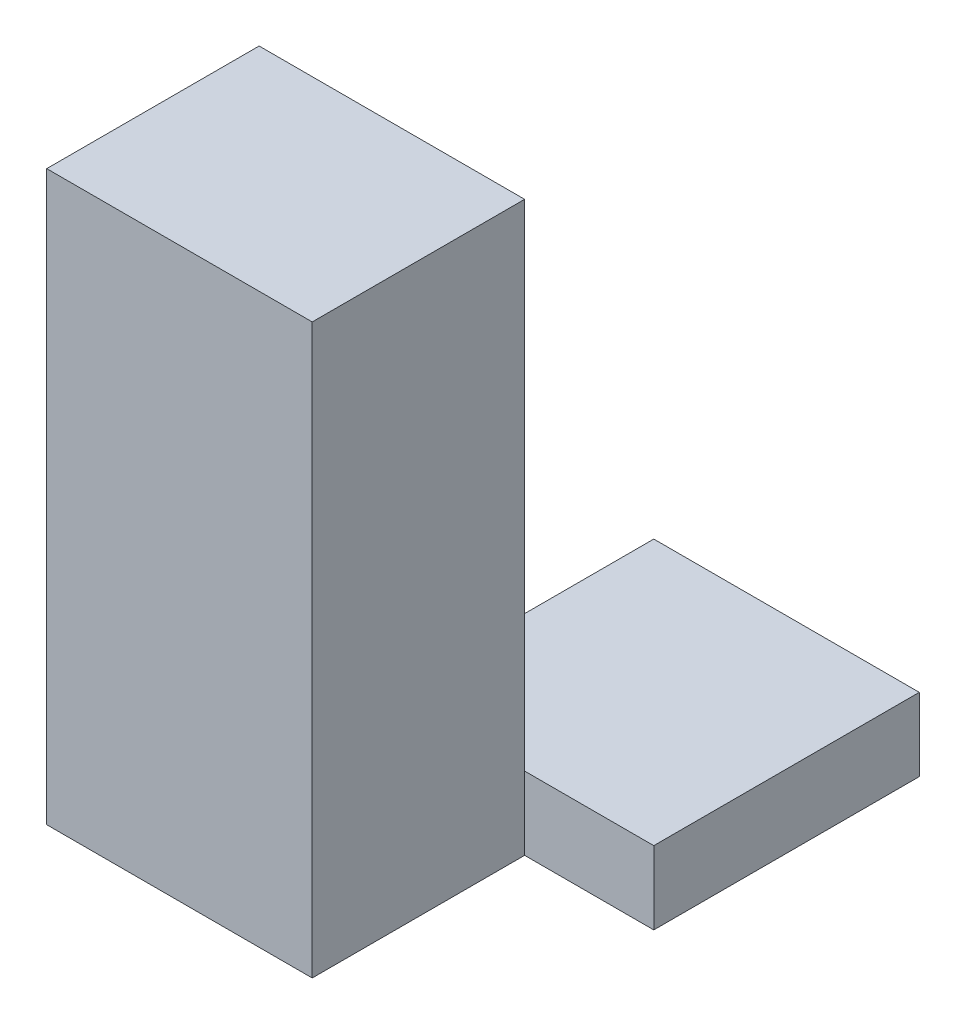
SolidWorks part; units mm, degrees
ref_plane "Front Plane" through (0, 0, 0) normal (0, 0, 1) x (1, 0, 0)
ref_plane "Top Plane" through (0, 0, 0) normal (0, 1, 0) x (1, 0, 0)
ref_plane "Right Plane" through (0, 0, 0) normal (1, 0, 0) x (0, 0, -1)
sketch "Sketch1" plane through (0, 0, 0) normal (0, 0, 1) x (1, 0, 0)
  line L1 (-19.457, -57.7267) -> (20.543, -57.7267)
  line L2 (-19.457, -57.7267) -> (-19.457, 27.8733)
  line L3 (-19.457, 27.8733) -> (20.543, 27.8733)
  line L4 (20.543, -57.7267) -> (20.543, 27.8733)
  line L5 (-19.457, -57.7267) -> (20.543, 27.8733) construction
  line L6 (-19.457, 27.8733) -> (20.543, -57.7267) construction
  point P0 (0.543, -14.9267)
  dimension "D1" = 40
  dimension "D2" = 85.6
extrude "Boss-Extrude1" add sketch "Sketch1" along normal blind 32
sketch "Sketch4" plane through (0, 0, 0) normal (1, 0, 0) x (0, 0, -1)
  line L1 (0, -57.7267) -> (40, -57.7267)
  line L2 (0, -57.7267) -> (0, -46.7267)
  line L3 (0, -46.7267) -> (40, -46.7267)
  line L4 (40, -57.7267) -> (40, -46.7267)
  dimension "D1" = 40
  dimension "D2" = 11
extrude "Boss-Extrude2" add sketch "Sketch4" along normal blind 40
sketch "Sketch5" plane through (0, -46.7267, 0) normal (0, 1, 0) x (1, 0, 0)
  line L0 (0, 40) -> (40, 0) construction
  line L1 (40, 40) -> (0, 0) construction
  circle A0 centre (18.156, 19.0476) radius 3.25
  dimension "D1" = 6.5
equation "\"F1_Length\"= 40mm"
equation "\"F1_Width\"= 40mm"
equation "\"F1_Thickness\"= 11mm"
equation "\"F2_Length\"= 85.6mm"
equation "\"F2_Width\"= 40mm"
equation "\"F2_Thickness\"= 32mm"
equation "\"Bolt_Clearance\"= 3.4mm"
equation "\"Shift_Clearance\"= 6.5mm"
